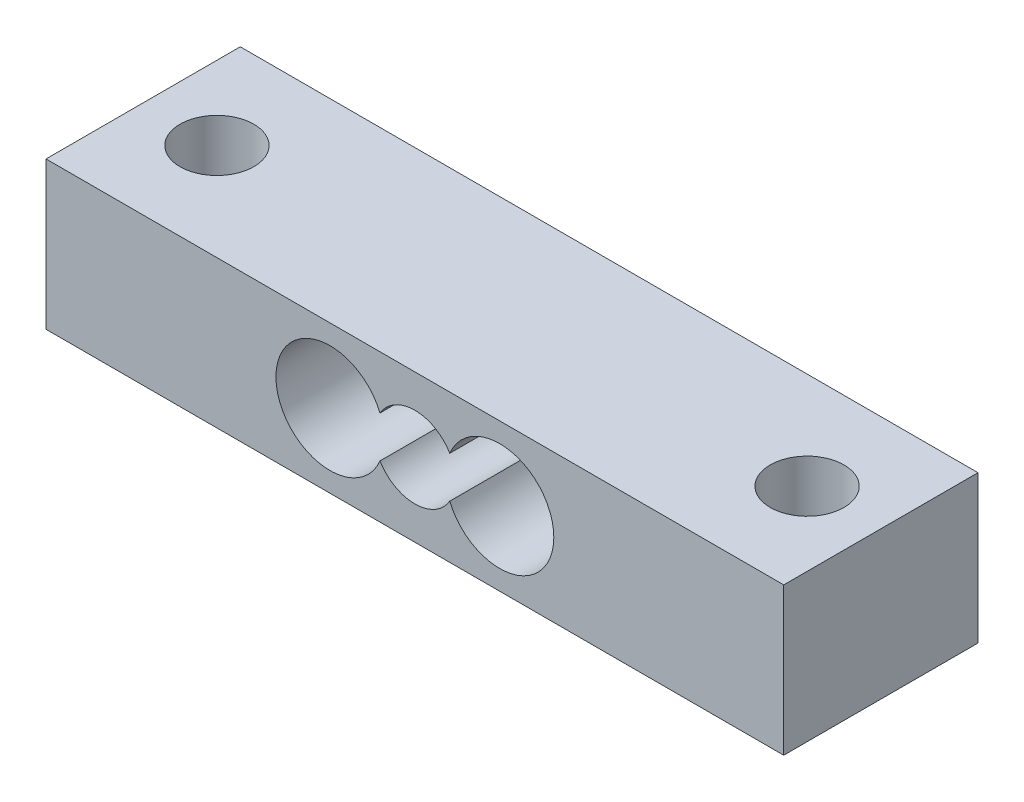
SolidWorks part; units mm, degrees
ref_plane "Front Plane" through (0, 0, 0) normal (0, 0, 1) x (1, 0, 0)
ref_plane "Top Plane" through (0, 0, 0) normal (0, 1, 0) x (1, 0, 0)
ref_plane "Right Plane" through (0, 0, 0) normal (1, 0, 0) x (0, 0, -1)
sketch "Sketch1" plane through (0, 0, 0) normal (0, 0, 1) x (1, 0, 0)
  line L0 (0, 3) -> (30, 3) construction
  line L1 (0, 0) -> (30, 0)
  line L2 (0, 0) -> (0, 6)
  line L3 (0, 6) -> (30, 6)
  line L4 (30, 0) -> (30, 6)
  line L5 (11.55, 5.2) -> (18.45, 5.2) construction
  line L6 (15, 5.2) -> (15, 6) construction
  arc A0 (13.5819, 3.8435) -> (13.5819, 2.1565) centre (11.55, 3) ccw
  arc A1 (16.4181, 2.1565) -> (16.4181, 3.8435) centre (18.45, 3) ccw
  arc A2 (13.5819, 2.1565) -> (16.4181, 2.1565) centre (15, 3) ccw
  arc A3 (13.35, 3) -> (13.5819, 2.1565) centre (15, 3) ccw construction
  arc A4 (13.5819, 3.8435) -> (13.35, 3) centre (15, 3) ccw construction
  arc A5 (13.75, 3) -> (13.5819, 3.8435) centre (11.55, 3) ccw construction
  arc A6 (13.5819, 2.1565) -> (13.75, 3) centre (11.55, 3) ccw construction
  arc A7 (16.25, 3) -> (16.4181, 2.1565) centre (18.45, 3) ccw construction
  arc A8 (16.4181, 3.8435) -> (16.25, 3) centre (18.45, 3) ccw construction
  arc A9 (16.4181, 3.8435) -> (13.5819, 3.8435) centre (15, 3) ccw
  arc A10 (16.65, 3) -> (16.4181, 3.8435) centre (15, 3) ccw construction
  arc A11 (16.4181, 2.1565) -> (16.65, 3) centre (15, 3) ccw construction
  point P17 (9.35, 3)
  point P18 (20.65, 3)
  dimension "D2" = 3.3
  dimension "D4" = 4.4
  dimension "D1" = 30
  dimension "D3" = 6
  dimension "D5" = 11.3
extrude "Boss-Extrude1" add sketch "Sketch1" along normal blind 7.9
sketch "Sketch2" plane through (0, 6, 0) normal (0, 1, 0) x (1, 0, 0)
  line L0 (1.5, -3.95) -> (28.5, -3.95) construction
  line L1 (0, -7.9) -> (0, 0) construction
  line L2 (30, -7.9) -> (30, 0) construction
  line L3 (15, -3.95) -> (15, 0) construction
  line L4 (30, 0) -> (0, 0) construction
  line L5 (0, -3.95) -> (1.5, -3.95) construction
  line L6 (28.5, -3.95) -> (30, -3.95) construction
  circle A0 centre (3, -3.95) radius 1.5
  circle A1 centre (27, -3.95) radius 1.5
  dimension "D1" = 3
  dimension "D2" = 27
extrude "Cut-Extrude1" cut sketch "Sketch2" against normal through all
